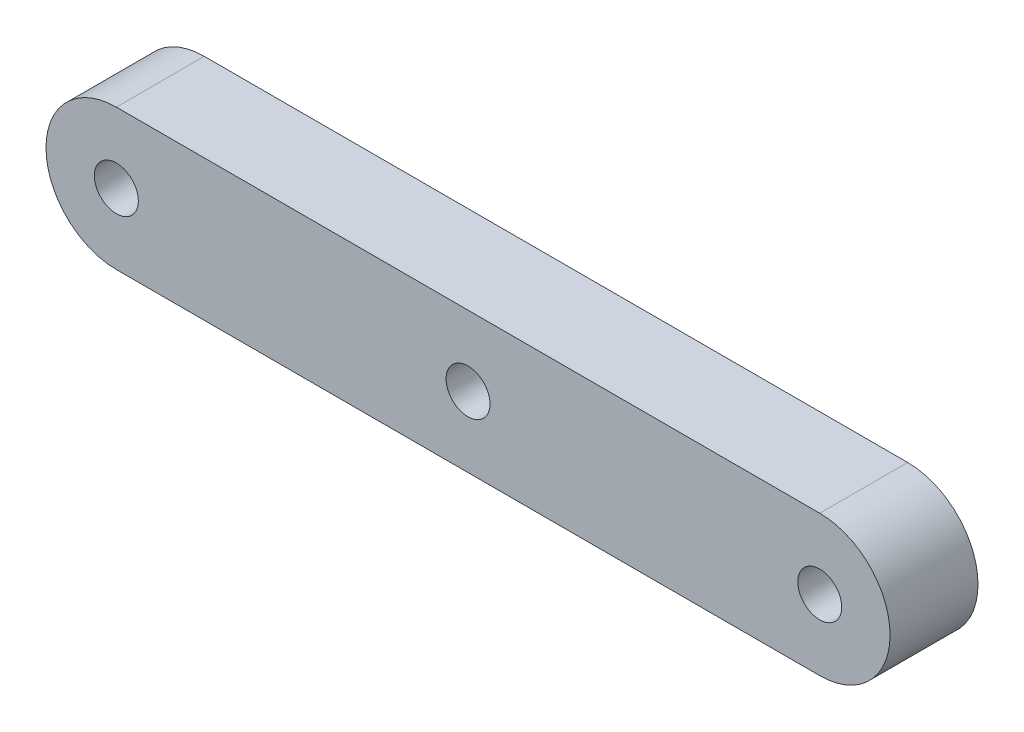
SolidWorks part; units mm, degrees
ref_plane "Front Plane" through (0, 0, 0) normal (0, 0, 1) x (1, 0, 0)
ref_plane "Top Plane" through (0, 0, 0) normal (0, 1, 0) x (1, 0, 0)
ref_plane "Right Plane" through (0, 0, 0) normal (1, 0, 0) x (0, 0, -1)
sketch "Sketch1" plane through (0, 0, 0) normal (0, 0, 1) x (1, 0, 0)
  line L0 (0.5886, 58.8403) -> (102.1886, 58.8403) construction
  line L1 (0.5886, 69.0003) -> (102.1886, 69.0003)
  line L2 (0.5886, 48.6803) -> (102.1886, 48.6803)
  arc A0 (0.5886, 69.0003) -> (0.5886, 48.6803) centre (0.5886, 58.8403) ccw
  arc A1 (102.1886, 48.6803) -> (102.1886, 69.0003) centre (102.1886, 58.8403) ccw
  circle A2 centre (51.3886, 58.8403) radius 3.175
  circle A3 centre (0.5886, 58.8403) radius 3.175
  circle A4 centre (102.1886, 58.8403) radius 3.175
  circle A5 centre (0.5886, 58.8403) radius 3.175 construction
  point P4 (51.3886, 58.8403)
  dimension "D1" = 10.16
extrude "Boss-Extrude1" add sketch "Sketch1" along normal blind 12.7
